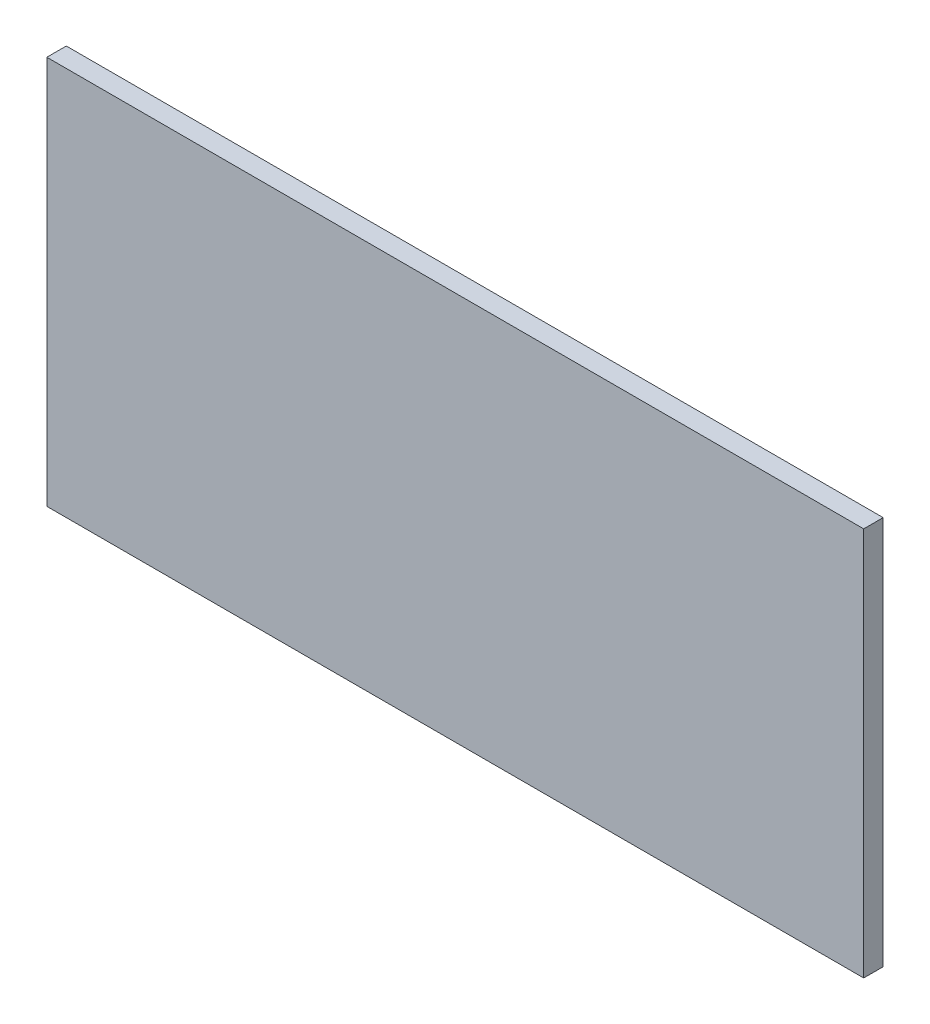
SolidWorks part; units mm, degrees
ref_plane "前视基准面" through (0, 0, 0) normal (0, 0, 1) x (1, 0, 0)
ref_plane "上视基准面" through (0, 0, 0) normal (0, 1, 0) x (1, 0, 0)
ref_plane "右视基准面" through (0, 0, 0) normal (1, 0, 0) x (0, 0, -1)
sketch "草图1" plane through (0, 0, 0) normal (0, 0, 1) x (1, 0, 0)
  line L0 (-58.8948, 0) -> (74.6601, 0) construction
  line L1 (-63, 30) -> (63, 30)
  line L2 (-63, 30) -> (-63, -30)
  line L3 (-63, -30) -> (63, -30)
  line L4 (63, 30) -> (63, -30)
  line L5 (0, 46.2468) -> (0, -45.6426) construction
  dimension "D1" = 126
  dimension "D2" = 60
extrude "凸台-拉伸1" add sketch "草图1" along normal blind 3
